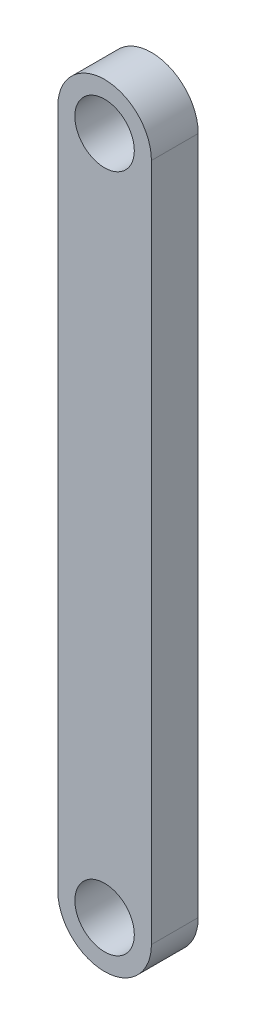
SolidWorks part; units mm, degrees
ref_plane "Front Plane" through (0, 0, 0) normal (0, 0, 1) x (1, 0, 0)
ref_plane "Top Plane" through (0, 0, 0) normal (0, 1, 0) x (1, 0, 0)
ref_plane "Right Plane" through (0, 0, 0) normal (1, 0, 0) x (0, 0, -1)
sketch "Sketch1" plane through (0, 0, 0) normal (0, 0, 1) x (1, 0, 0)
  line L0 (0, 0) -> (0, 145) construction
  line L1 (-10, 0) -> (-10, 145)
  line L2 (10, 0) -> (10, 145)
  arc A0 (-10, 0) -> (10, 0) centre (0, 0) ccw
  arc A1 (10, 145) -> (-10, 145) centre (0, 145) ccw
  point P3 (0, 72.5)
  dimension "D1" = 145
  dimension "D2" = 20
extrude "Boss-Extrude1" add sketch "Sketch1" along normal blind 10
sketch "Sketch2" plane through (0, 0, 10) normal (0, 0, 1) x (1, 0, 0)
  circle A0 centre (0, 145) radius 6.35
  circle A1 centre (0, 0) radius 6.35
  dimension "D1" = 12.7
  dimension "D2" = 12.7
extrude "Cut-Extrude1" cut sketch "Sketch2" against normal through all
